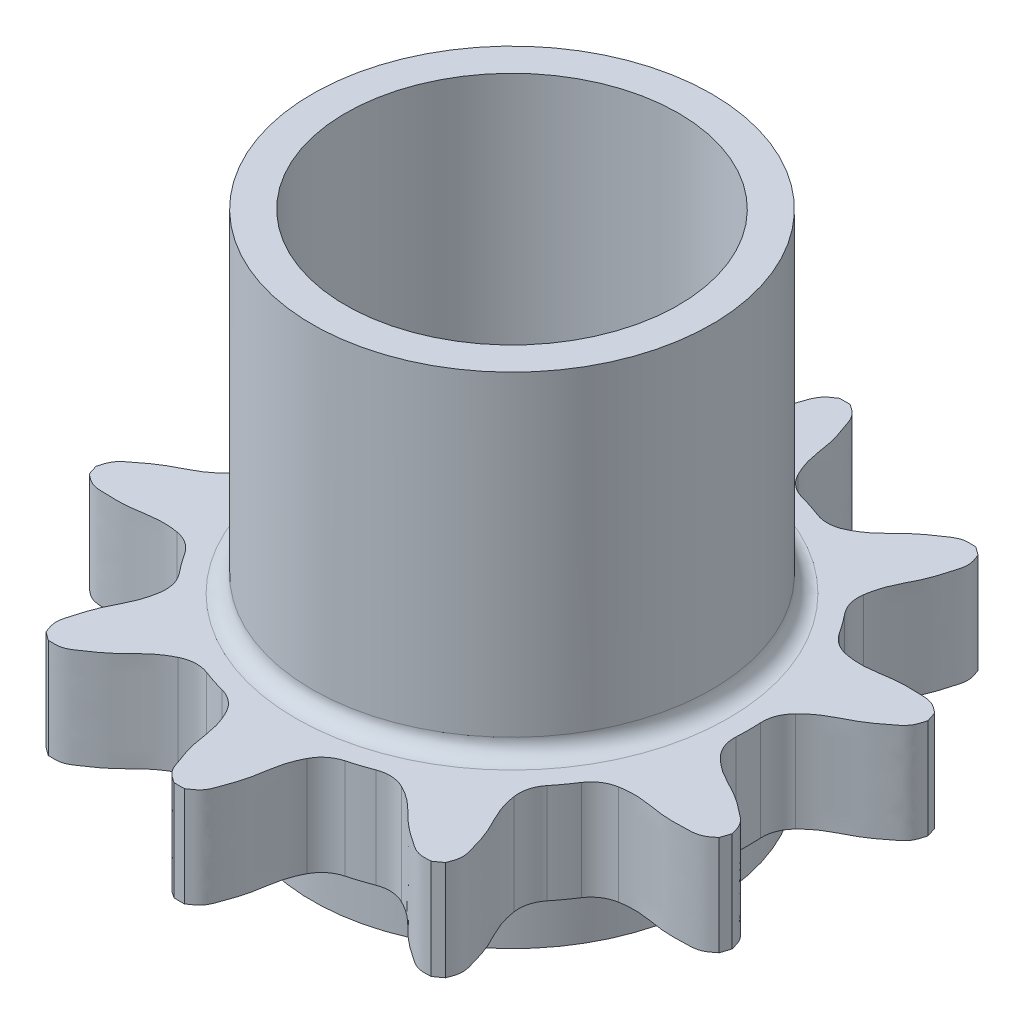
SolidWorks part; units mm, degrees
ref_plane "Front Plane" through (0, 0, 0) normal (0, 0, 1) x (1, 0, 0)
ref_plane "Top Plane" through (0, 0, 0) normal (0, 1, 0) x (1, 0, 0)
ref_plane "Right Plane" through (0, 0, 0) normal (1, 0, 0) x (0, 0, -1)
sketch "Sketch1" plane through (0, 0, 0) normal (0, 1, 0) x (1, 0, 0)
  circle A0 centre (0, 0) radius 5
  circle A1 centre (0, 0) radius 6
  arc A2 (-3.3515, -6.6776) -> (-2.5431, -6.6366) centre (-2.901, -7.5704) cw
  arc A3 (-7.0976, 0.3679) -> (-7.0976, -0.3679) centre (0, 0) ccw
  arc A4 (-5.3151, -5.2509) -> (-5.5259, -4.4695) centre (-6.3034, -5.0983) ccw
  arc A5 (-6.004, -7.997) -> (-5.7502, -8.1814) centre (0, 0) ccw
  arc A6 (-6.6364, -3.4323) -> (-5.9583, -3.8743) centre (-6.7967, -4.4194) cw
  arc A7 (-7.3864, -1.1239) -> (-7.0976, -0.3679) centre (-8.0963, -0.4196) ccw
  arc A8 (-0.1569, -9.9988) -> (0.1569, -9.9988) centre (0, 0) ccw
  arc A9 (-9.5579, -2.9406) -> (-9.4609, -3.239) centre (0, 0) ccw
  arc A10 (-7.3864, 1.1239) -> (-7.0976, 0.3679) centre (-8.0963, 0.4196) cw
  arc A11 (-5.9583, -3.8743) -> (-5.5259, -4.4695) centre (0, 0) ccw
  arc A12 (-2.5431, -6.6366) -> (-1.8434, -6.8639) centre (0, 0) ccw
  arc A13 (1.8434, -6.8639) -> (2.5431, -6.6366) centre (0, 0) ccw
  arc A14 (5.5259, -4.4695) -> (5.9583, -3.8743) centre (0, 0) ccw
  arc A15 (7.0976, -0.3679) -> (7.0976, 0.3679) centre (0, 0) ccw
  arc A16 (5.9583, 3.8743) -> (5.5259, 4.4695) centre (0, 0) ccw
  arc A17 (2.5431, 6.6366) -> (1.8434, 6.8639) centre (0, 0) ccw
  arc A18 (-6.6364, 3.4323) -> (-5.9583, 3.8743) centre (-6.7967, 4.4194) ccw
  arc A19 (-9.4609, 3.239) -> (-9.5579, 2.9406) centre (0, 0) ccw
  arc A20 (-5.3151, 5.2509) -> (-5.5259, 4.4695) centre (-6.3034, 5.0983) cw
  arc A21 (-3.3515, 6.6776) -> (-2.5431, 6.6366) centre (-2.901, 7.5704) ccw
  arc A22 (-5.7502, 8.1814) -> (-6.004, 7.997) centre (0, 0) ccw
  arc A23 (-1.2136, 7.3722) -> (-1.8434, 6.8639) centre (-2.1028, 7.8297) cw
  arc A24 (-1.2136, -7.3722) -> (-1.8434, -6.8639) centre (-2.1028, -7.8297) ccw
  arc A25 (1.2136, -7.3722) -> (1.8434, -6.8639) centre (2.1028, -7.8297) cw
  arc A26 (1.2136, 7.3722) -> (1.8434, 6.8639) centre (2.1028, 7.8297) ccw
  arc A27 (0.1569, 9.9988) -> (-0.1569, 9.9988) centre (0, 0) ccw
  arc A28 (3.3515, 6.6776) -> (2.5431, 6.6366) centre (2.901, 7.5704) cw
  arc A29 (5.3151, 5.2509) -> (5.5259, 4.4695) centre (6.3034, 5.0983) ccw
  arc A30 (6.004, 7.997) -> (5.7502, 8.1814) centre (0, 0) ccw
  arc A31 (6.6364, 3.4323) -> (5.9583, 3.8743) centre (6.7967, 4.4194) cw
  arc A32 (7.3864, 1.1239) -> (7.0976, 0.3679) centre (8.0963, 0.4196) ccw
  arc A33 (9.5579, 2.9406) -> (9.4609, 3.239) centre (0, 0) ccw
  arc A34 (7.3864, -1.1239) -> (7.0976, -0.3679) centre (8.0963, -0.4196) cw
  arc A35 (6.6364, -3.4323) -> (5.9583, -3.8743) centre (6.7967, -4.4194) ccw
  arc A36 (9.4609, -3.239) -> (9.5579, -2.9406) centre (0, 0) ccw
  arc A37 (5.3151, -5.2509) -> (5.5259, -4.4695) centre (6.3034, -5.0983) cw
  arc A38 (3.3515, -6.6776) -> (2.5431, -6.6366) centre (2.901, -7.5704) ccw
  arc A39 (5.7502, -8.1814) -> (6.004, -7.997) centre (0, 0) ccw
  arc A40 (-1.8434, 6.8639) -> (-2.5431, 6.6366) centre (0, 0) ccw
  arc A41 (-5.5259, 4.4695) -> (-5.9583, 3.8743) centre (0, 0) ccw
  spline S0 degree 3 poles (-6.004, -7.997) (-6.006, -7.9918) (-6.0495, -7.8781) (-6.1535, -7.6065) (-6.0097, -7.138) (-5.8221, -6.4844) (-5.4423, -5.889) (-5.3392, -5.4071) (-5.3151, -5.2509) knots -0.004717 -0.004717 -0.004717 -0.004717 0.000118 0.105683 0.243127 0.421867 0.719007 0.859817 0.859817 0.859817 0.859817
  spline S1 degree 3 poles (-5.7502, -8.1814) (-5.7447, -8.1817) (-5.6231, -8.1879) (-5.3327, -8.2029) (-4.9315, -7.9214) (-4.3679, -7.5409) (-3.919, -6.9958) (-3.4925, -6.7488) (-3.3515, -6.6776) knots -0.004717 -0.004717 -0.004717 -0.004717 0.000118 0.105683 0.243127 0.421867 0.719007 0.859817 0.859817 0.859817 0.859817
  spline S2 degree 3 poles (-9.5579, -2.9406) (-9.5564, -2.9352) (-9.5248, -2.8177) (-9.4493, -2.5369) (-9.0576, -2.2423) (-8.5216, -1.8239) (-7.8644, -1.5654) (-7.4977, -1.2361) (-7.3864, -1.1239) knots -0.004717 -0.004717 -0.004717 -0.004717 0.000118 0.105683 0.243127 0.421867 0.719007 0.859817 0.859817 0.859817 0.859817
  spline S3 degree 3 poles (-9.4609, -3.239) (-9.4566, -3.2425) (-9.3619, -3.319) (-9.1358, -3.5017) (-8.6457, -3.5099) (-7.9662, -3.5333) (-7.2826, -3.3562) (-6.7923, -3.407) (-6.6364, -3.4323) knots -0.004717 -0.004717 -0.004717 -0.004717 0.000118 0.105683 0.243127 0.421867 0.719007 0.859817 0.859817 0.859817 0.859817
  spline S4 degree 3 poles (-9.4609, 3.239) (-9.4566, 3.2425) (-9.3619, 3.319) (-9.1358, 3.5017) (-8.6457, 3.5099) (-7.9662, 3.5333) (-7.2826, 3.3562) (-6.7923, 3.407) (-6.6364, 3.4323) knots -0.004717 -0.004717 -0.004717 -0.004717 0.000118 0.105683 0.243127 0.421867 0.719007 0.859817 0.859817 0.859817 0.859817
  spline S5 degree 3 poles (-9.5579, 2.9406) (-9.5564, 2.9352) (-9.5248, 2.8177) (-9.4493, 2.5369) (-9.0576, 2.2423) (-8.5216, 1.8239) (-7.8644, 1.5654) (-7.4977, 1.2361) (-7.3864, 1.1239) knots -0.004717 -0.004717 -0.004717 -0.004717 0.000118 0.105683 0.243127 0.421867 0.719007 0.859817 0.859817 0.859817 0.859817
  spline S6 degree 3 poles (-5.7502, 8.1814) (-5.7447, 8.1817) (-5.6231, 8.1879) (-5.3327, 8.2029) (-4.9315, 7.9214) (-4.3679, 7.5409) (-3.919, 6.9958) (-3.4925, 6.7488) (-3.3515, 6.6776) knots -0.004717 -0.004717 -0.004717 -0.004717 0.000118 0.105683 0.243127 0.421867 0.719007 0.859817 0.859817 0.859817 0.859817
  spline S7 degree 3 poles (-6.004, 7.997) (-6.006, 7.9918) (-6.0495, 7.8781) (-6.1535, 7.6065) (-6.0097, 7.138) (-5.8221, 6.4844) (-5.4423, 5.889) (-5.3392, 5.4071) (-5.3151, 5.2509) knots -0.004717 -0.004717 -0.004717 -0.004717 0.000118 0.105683 0.243127 0.421867 0.719007 0.859817 0.859817 0.859817 0.859817
  spline S8 degree 3 poles (0.1569, -9.9988) (0.1615, -9.9957) (0.2636, -9.9293) (0.5072, -9.7707) (0.6664, -9.3072) (0.8987, -8.6681) (0.9415, -7.9632) (1.1413, -7.5127) (1.2136, -7.3722) knots -0.004717 -0.004717 -0.004717 -0.004717 0.000118 0.105683 0.243127 0.421867 0.719007 0.859817 0.859817 0.859817 0.859817
  spline S9 degree 3 poles (-0.1569, -9.9988) (-0.1615, -9.9957) (-0.2636, -9.9293) (-0.5072, -9.7707) (-0.6664, -9.3072) (-0.8987, -8.6681) (-0.9415, -7.9632) (-1.1413, -7.5127) (-1.2136, -7.3722) knots -0.004717 -0.004717 -0.004717 -0.004717 0.000118 0.105683 0.243127 0.421867 0.719007 0.859817 0.859817 0.859817 0.859817
  spline S10 degree 3 poles (0.1569, 9.9988) (0.1615, 9.9957) (0.2636, 9.9293) (0.5072, 9.7707) (0.6664, 9.3072) (0.8987, 8.6681) (0.9415, 7.9632) (1.1413, 7.5127) (1.2136, 7.3722) knots -0.004717 -0.004717 -0.004717 -0.004717 0.000118 0.105683 0.243127 0.421867 0.719007 0.859817 0.859817 0.859817 0.859817
  spline S11 degree 3 poles (-0.1569, 9.9988) (-0.1615, 9.9957) (-0.2636, 9.9293) (-0.5072, 9.7707) (-0.6664, 9.3072) (-0.8987, 8.6681) (-0.9415, 7.9632) (-1.1413, 7.5127) (-1.2136, 7.3722) knots -0.004717 -0.004717 -0.004717 -0.004717 0.000118 0.105683 0.243127 0.421867 0.719007 0.859817 0.859817 0.859817 0.859817
  spline S12 degree 3 poles (6.004, 7.997) (6.006, 7.9918) (6.0495, 7.8781) (6.1535, 7.6065) (6.0097, 7.138) (5.8221, 6.4844) (5.4423, 5.889) (5.3392, 5.4071) (5.3151, 5.2509) knots -0.004717 -0.004717 -0.004717 -0.004717 0.000118 0.105683 0.243127 0.421867 0.719007 0.859817 0.859817 0.859817 0.859817
  spline S13 degree 3 poles (5.7502, 8.1814) (5.7447, 8.1817) (5.6231, 8.1879) (5.3327, 8.2029) (4.9315, 7.9214) (4.3679, 7.5409) (3.919, 6.9958) (3.4925, 6.7488) (3.3515, 6.6776) knots -0.004717 -0.004717 -0.004717 -0.004717 0.000118 0.105683 0.243127 0.421867 0.719007 0.859817 0.859817 0.859817 0.859817
  spline S14 degree 3 poles (9.5579, 2.9406) (9.5564, 2.9352) (9.5248, 2.8177) (9.4493, 2.5369) (9.0576, 2.2423) (8.5216, 1.8239) (7.8644, 1.5654) (7.4977, 1.2361) (7.3864, 1.1239) knots -0.004717 -0.004717 -0.004717 -0.004717 0.000118 0.105683 0.243127 0.421867 0.719007 0.859817 0.859817 0.859817 0.859817
  spline S15 degree 3 poles (9.4609, 3.239) (9.4566, 3.2425) (9.3619, 3.319) (9.1358, 3.5017) (8.6457, 3.5099) (7.9662, 3.5333) (7.2826, 3.3562) (6.7923, 3.407) (6.6364, 3.4323) knots -0.004717 -0.004717 -0.004717 -0.004717 0.000118 0.105683 0.243127 0.421867 0.719007 0.859817 0.859817 0.859817 0.859817
  spline S16 degree 3 poles (9.4609, -3.239) (9.4566, -3.2425) (9.3619, -3.319) (9.1358, -3.5017) (8.6457, -3.5099) (7.9662, -3.5333) (7.2826, -3.3562) (6.7923, -3.407) (6.6364, -3.4323) knots -0.004717 -0.004717 -0.004717 -0.004717 0.000118 0.105683 0.243127 0.421867 0.719007 0.859817 0.859817 0.859817 0.859817
  spline S17 degree 3 poles (9.5579, -2.9406) (9.5564, -2.9352) (9.5248, -2.8177) (9.4493, -2.5369) (9.0576, -2.2423) (8.5216, -1.8239) (7.8644, -1.5654) (7.4977, -1.2361) (7.3864, -1.1239) knots -0.004717 -0.004717 -0.004717 -0.004717 0.000118 0.105683 0.243127 0.421867 0.719007 0.859817 0.859817 0.859817 0.859817
  spline S18 degree 3 poles (5.7502, -8.1814) (5.7447, -8.1817) (5.6231, -8.1879) (5.3327, -8.2029) (4.9315, -7.9214) (4.3679, -7.5409) (3.919, -6.9958) (3.4925, -6.7488) (3.3515, -6.6776) knots -0.004717 -0.004717 -0.004717 -0.004717 0.000118 0.105683 0.243127 0.421867 0.719007 0.859817 0.859817 0.859817 0.859817
  spline S19 degree 3 poles (6.004, -7.997) (6.006, -7.9918) (6.0495, -7.8781) (6.1535, -7.6065) (6.0097, -7.138) (5.8221, -6.4844) (5.4423, -5.889) (5.3392, -5.4071) (5.3151, -5.2509) knots -0.004717 -0.004717 -0.004717 -0.004717 0.000118 0.105683 0.243127 0.421867 0.719007 0.859817 0.859817 0.859817 0.859817
extrude "Extrude1" add sketch "Sketch1" against normal blind 3
sketch "Sketch2" plane through (0, -3, 0) normal (0, -1, 0) x (1, 0, 0)
  circle A0 centre (0, 0) radius 5
  circle A1 centre (0, 0) radius 6
extrude "Extrude2" add sketch "Sketch2" along normal blind 2 and the other way blind 13
fillet "Fillet1" radius 0.5 2 edges at (0, 0, 6) (0, -3, 6)
